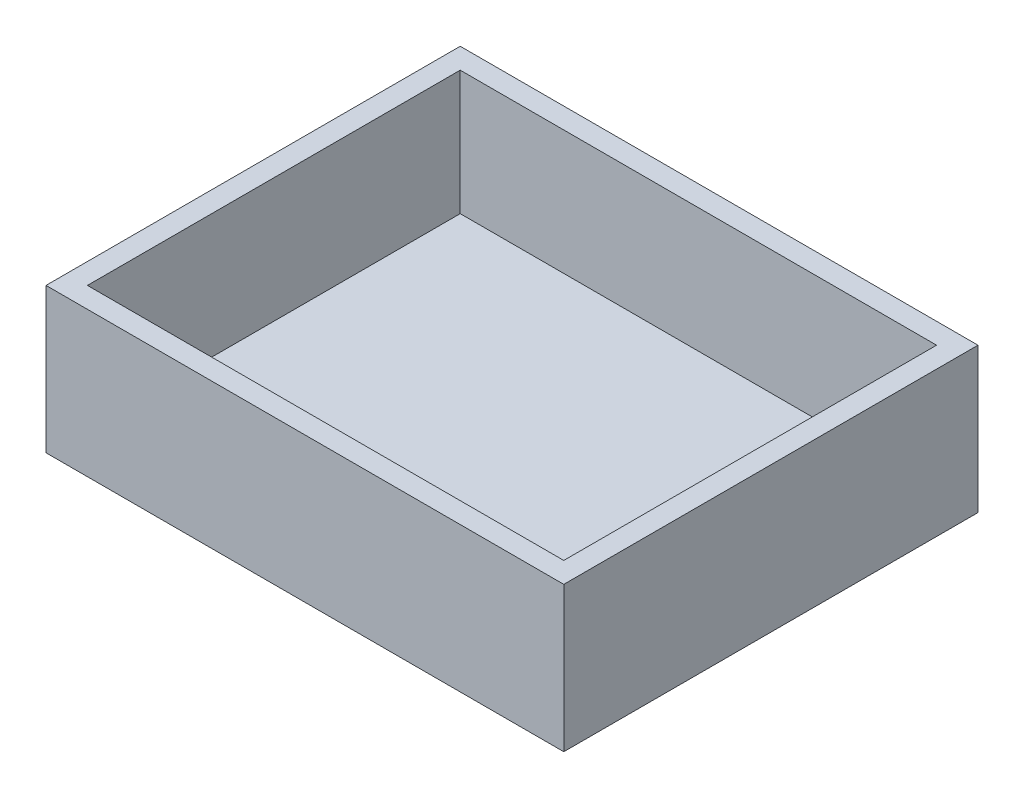
SolidWorks part; units mm, degrees
material "1.4003 (X2CrNi12)"
ref_plane "Alzado" through (0, 0, 0) normal (0, 0, 1) x (1, 0, 0)
ref_plane "Planta" through (0, 0, 0) normal (0, 1, 0) x (1, 0, 0)
ref_plane "Vista lateral" through (0, 0, 0) normal (1, 0, 0) x (0, 0, -1)
sketch "Croquis1" plane through (0, 0, 0) normal (0, 1, 0) x (1, 0, 0)
  line L1 (-125, 100) -> (125, 100)
  line L2 (-125, 100) -> (-125, -100)
  line L3 (-125, -100) -> (125, -100)
  line L4 (125, 100) -> (125, -100)
  line L5 (-125, 100) -> (125, -100) construction
  line L6 (-125, -100) -> (125, 100) construction
  point P0 (0, 0)
  dimension "D1" = 250
  dimension "D2" = 200
extrude "Saliente-Extruir1" add sketch "Croquis1" along normal blind 10
sketch "Croquis2" plane through (0, 10, 0) normal (0, 1, 0) x (1, 0, 0)
  line L1 (-125, 100) -> (125, 100)
  line L2 (-125, 100) -> (-125, -100)
  line L3 (-125, -100) -> (125, -100)
  line L4 (125, 100) -> (125, -100)
  line L7 (-115, 90) -> (115, 90)
  line L8 (-115, 90) -> (-115, -90)
  line L9 (-115, -90) -> (115, -90)
  line L10 (115, 90) -> (115, -90)
  point P0 (0, 0)
  point P7 (0, 0)
  dimension "D1" = 10
  dimension "D2" = 10
  dimension "D3" = 10
  dimension "D4" = 10
extrude "Saliente-Extruir2" add sketch "Croquis2" along normal blind 60
